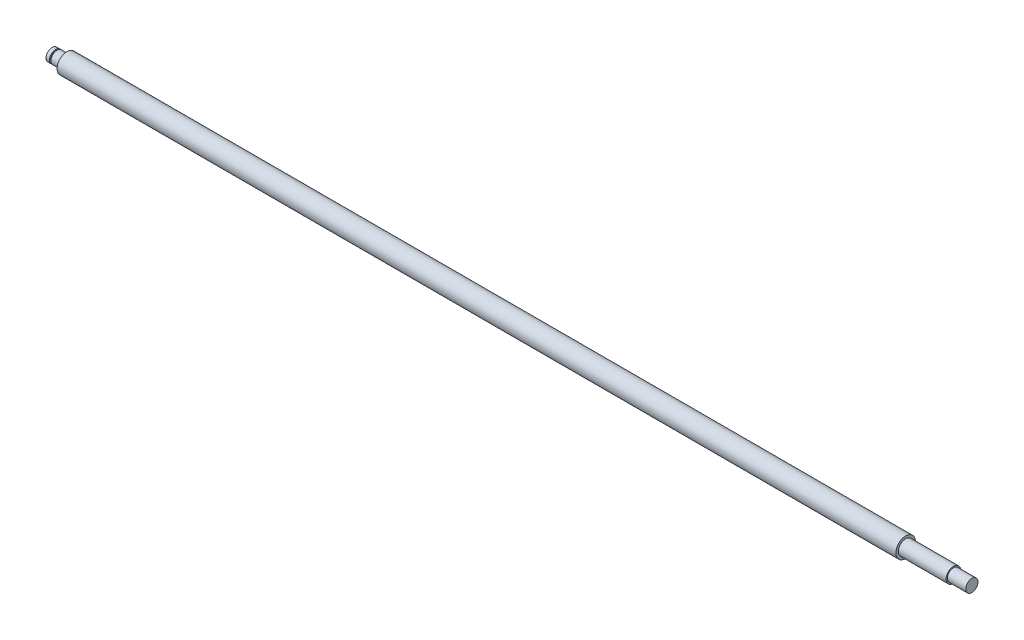
SolidWorks part; units mm, degrees
ref_plane "Plan de face" through (0, 0, 0) normal (0, 0, 1) x (1, 0, 0)
ref_plane "Plan de dessus" through (0, 0, 0) normal (0, 1, 0) x (1, 0, 0)
ref_plane "Plan de droite" through (0, 0, 0) normal (1, 0, 0) x (0, 0, -1)
sketch "Esquisse1" plane through (0, 0, 0) normal (0, 0, 1) x (1, 0, 0)
  line L0 (-89.4006, 0) -> (1216.033, 0) construction
  line L1 (-88.2233, 0) -> (-88.2233, 5)
  line L2 (-88.2233, 5) -> (-85.3699, 5)
  line L3 (-85.3699, 5) -> (-85.3699, 4)
  line L4 (-85.3699, 4) -> (-84.2199, 4)
  line L5 (-84.2199, 4) -> (-84.2199, 5)
  line L6 (-84.2199, 5) -> (-76.2199, 5)
  line L7 (-76.2199, 5) -> (-76.2199, 8)
  line L8 (-76.2199, 8) -> (607.7801, 8)
  line L9 (607.7801, 8) -> (607.7801, 6)
  line L10 (607.7801, 6) -> (634.7801, 6)
  line L11 (634.7801, 6) -> (646.7801, 6)
  line L12 (646.7801, 6) -> (646.7801, 5)
  line L13 (646.7801, 5) -> (661.7801, 5)
  line L14 (661.7801, 5) -> (661.7801, 0)
  line L15 (-88.2233, 0) -> (661.7801, 0)
  dimension "D1" = 5
  dimension "D2" = 2.8534
  dimension "D3" = 1
  dimension "D4" = 1.15
  dimension "D5" = 8
  dimension "D6" = 3
  dimension "D7" = 1
  dimension "D8" = 684
  dimension "D9" = 2
  dimension "D10" = 27
  dimension "D11" = 12
  dimension "D12" = 1
  dimension "D13" = 15
  dimension "D14" = 5
revolve "Révolution1" add sketch "Esquisse1" angle 360 about L0
